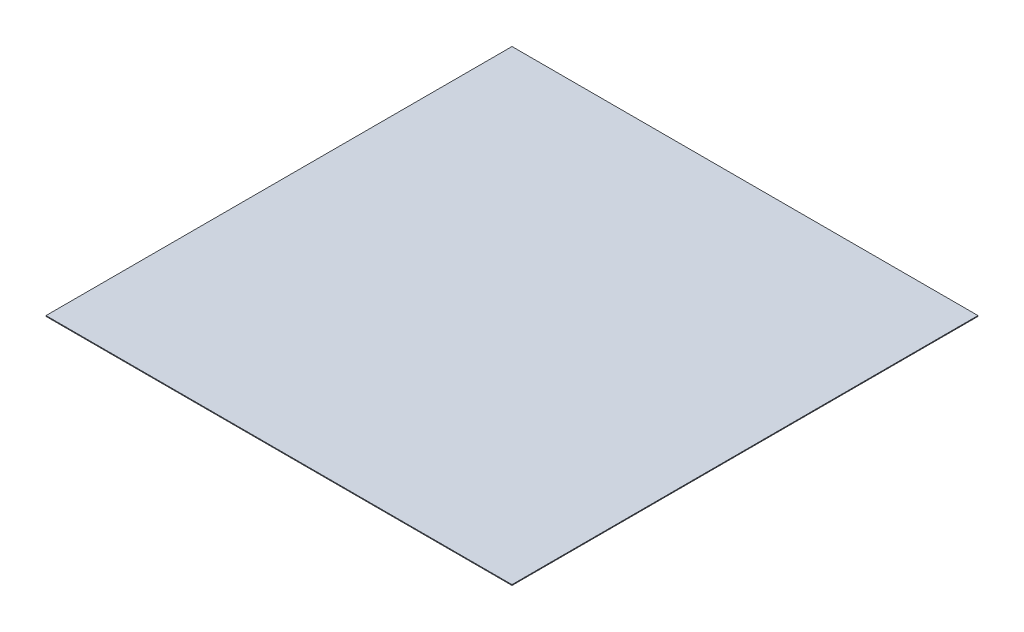
SolidWorks part; units mm, degrees
material "Alloy Steel"
ref_plane "Front Plane" through (0, 0, 0) normal (0, 0, 1) x (1, 0, 0)
ref_plane "Top Plane" through (0, 0, 0) normal (0, 1, 0) x (1, 0, 0)
ref_plane "Right Plane" through (0, 0, 0) normal (1, 0, 0) x (0, 0, -1)
sketch "Sketch1" plane through (0, 0, 0) normal (0, 1, 0) x (1, 0, 0)
  line L1 (-15, 15) -> (15, 15)
  line L2 (-15, 15) -> (-15, -15)
  line L3 (-15, -15) -> (15, -15)
  line L4 (15, 15) -> (15, -15)
  line L5 (-15, 15) -> (15, -15) construction
  line L6 (-15, -15) -> (15, 15) construction
  point P0 (0, 0)
  dimension "D1" = 30
  dimension "D2" = 30
extrude "Boss-Extrude1" add sketch "Sketch1" along normal blind 0.05
